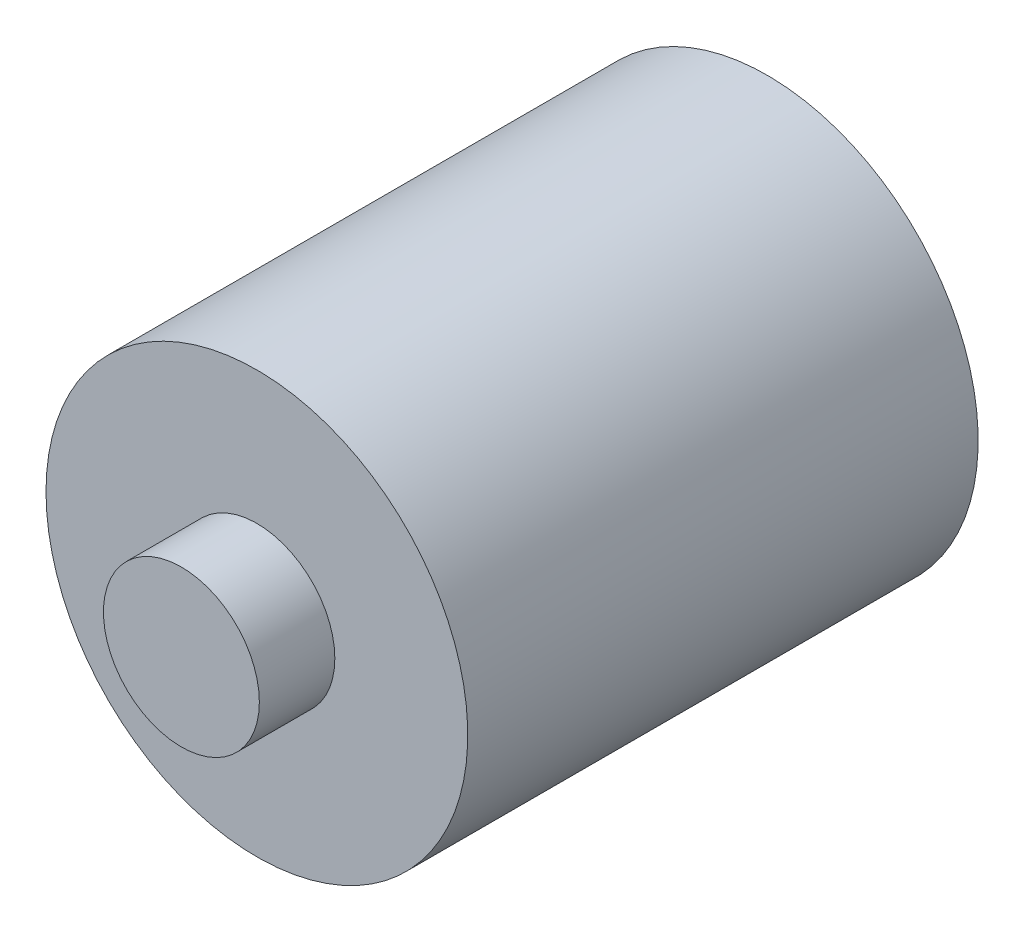
SolidWorks part; units mm, degrees
ref_plane "前基準面" through (0, 0, 0) normal (0, 0, 1) x (1, 0, 0)
ref_plane "上基準面" through (0, 0, 0) normal (0, 1, 0) x (1, 0, 0)
ref_plane "右基準面" through (0, 0, 0) normal (1, 0, 0) x (0, 0, -1)
sketch "草圖1" plane through (0, 0, 0) normal (0, 0, 1) x (1, 0, 0)
  circle A0 centre (0, 0) radius 12.85
  dimension "D1" = 25.7
extrude "伸長1" add sketch "草圖1" along normal blind 31.1
sketch "草圖2" plane through (0, 0, 31.1) normal (0, 0, 1) x (1, 0, 0)
  circle A0 centre (0, 0) radius 4.75
  dimension "D1" = 9.5
extrude "伸長2" add sketch "草圖2" along normal blind 4.6
sketch "草圖3" plane through (0, 0, 0) normal (0, 0, -1) x (-1, 0, 0)
  circle A0 centre (0, 0) radius 6
  dimension "D1" = 12
extrude "伸長3" cut sketch "草圖3" against normal blind 16
